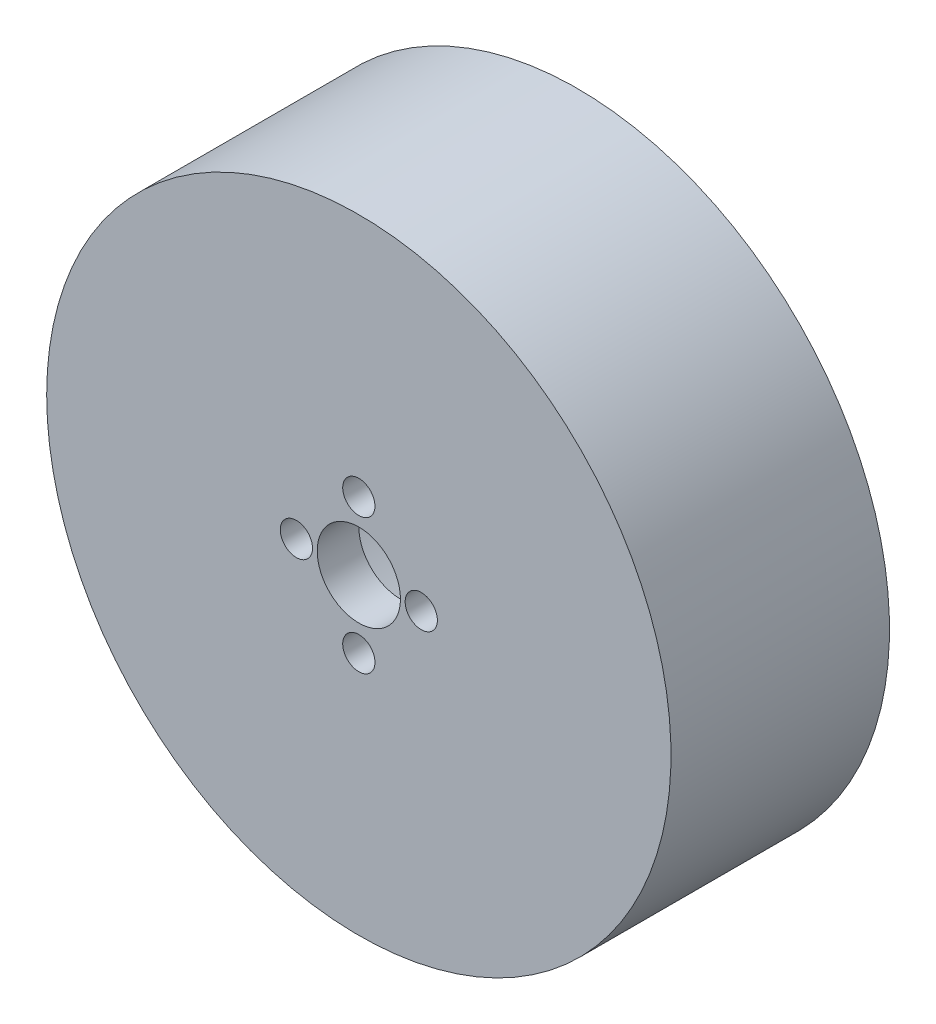
SolidWorks part; units mm, degrees
ref_plane "Front Plane" through (0, 0, 0) normal (0, 0, 1) x (1, 0, 0)
ref_plane "Top Plane" through (0, 0, 0) normal (0, 1, 0) x (1, 0, 0)
ref_plane "Right Plane" through (0, 0, 0) normal (1, 0, 0) x (0, 0, -1)
sketch "Sketch1" plane through (0, 0, 0) normal (0, 0, 1) x (1, 0, 0)
  circle A0 centre (0, 0) radius 30
  dimension "D1" = 60
extrude "Boss-Extrude1" add sketch "Sketch1" along normal mid plane 21
sketch "Sketch2" plane through (0, 0, 10.5) normal (0, 0, 1) x (1, 0, 0)
  line L1 (0, -6.5) -> (6, 0) construction
  line L2 (0, -6.5) -> (-6, 0) construction
  line L3 (-6, 0) -> (0, 6.5) construction
  line L4 (6, 0) -> (0, 6.5) construction
  line L5 (0, -6.5) -> (0, 6.5) construction
  line L6 (-6, 0) -> (6, 0) construction
  circle A0 centre (-6, 0) radius 1.55
  circle A4 centre (0, 6.5) radius 1.55
  circle A5 centre (6, 0) radius 1.55
  circle A6 centre (0, -6.5) radius 1.55
  circle A7 centre (0, 0) radius 4
  dimension "D2" = 3.1
  dimension "D4" = 8
  dimension "D1" = 13
  dimension "D3" = 12
extrude "Cut-Extrude1" cut sketch "Sketch2" against normal blind 10
sketch "Sketch3" plane through (0, 0, -10.5) normal (0, 0, -1) x (-1, 0, 0)
  circle A0 centre (0, 0) radius 21
  dimension "D1" = 42
extrude "Cut-Extrude2" cut sketch "Sketch3" against normal blind 17
